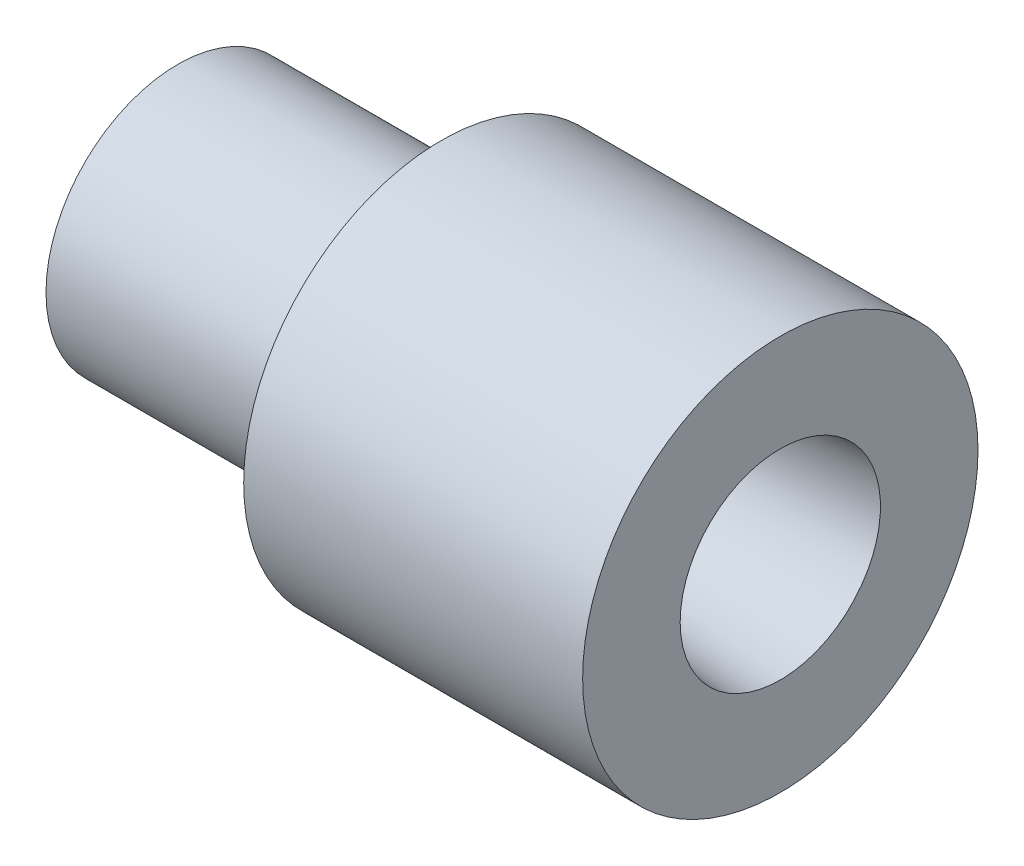
SolidWorks part; units mm, degrees
ref_plane "Front Plane" through (0, 0, 0) normal (0, 0, 1) x (1, 0, 0)
ref_plane "Top Plane" through (0, 0, 0) normal (0, 1, 0) x (1, 0, 0)
ref_plane "Right Plane" through (0, 0, 0) normal (1, 0, 0) x (0, 0, -1)
sketch "Sketch1" plane through (0, 0, 0) normal (0, 1, 0) x (1, 0, 0)
  line L0 (0, 0) -> (0, 2.286) construction
  line L1 (0, 2.286) -> (0, 6.35)
  line L2 (12.7, 9.525) -> (29.0323, 9.525)
  line L3 (29.0323, 9.525) -> (29.0323, 4.826)
  line L4 (29.0323, 4.826) -> (0, 2.286)
  line L5 (0, 0) -> (29.0323, 0) construction
  line L6 (29.0323, 0) -> (29.0323, 4.826) construction
  line L8 (12.7, 6.35) -> (12.7, 9.525)
  line L12 (0, 6.35) -> (12.7, 6.35)
  dimension "D1" = 2.286
  dimension "D2" = 4.826
  dimension "D3" = 5
  dimension "D4" = 9.525
  dimension "D5" = 6.35
  dimension "D6" = 12.7
revolve "Revolve1" add sketch "Sketch1" angle 360 about L5
equation "\"z\"= 8\t\t\t\t'number of blades"
equation "\"de\"= 0.43in\t\t\t'entrance eye diameter"
equation "\"de_length\"= 10mm\t\t'entrance eye consistent length"
equation "\"d_exit\"= 0.18in \t\t'throat aka d1"
equation "\"d2\"= 2.1in \t\t\t'outer diameter of the impeller"
equation "\"b2\"= .2in\t\t\t'tip height from disc surface at d2; slightly higher than d_exit"
equation "\"b1\"= \"b2\" + (\"d2\"/2 - \"de\"/2)*tan(\"theta\") \t\t\t'tip height from disc surface at inlet eye"
equation "\"theta\"= 12\t\t\t'angle of blades from inner to outer "
equation "\"ae\"= 3.14*(\"de\"^2)/4\t\t'entrance eye area'"
equation "\"ce\"= 3.14*\"de\"\t\t'entrance eye circumference"
equation "\"av_ratio\"= .325\t\t'ratio of av/ae at N_s of 470, range is .275 to .375, .325 ideal. High ratio means bigger area means smaller blades"
equation "\"av\"= \"ae\"*\"av_ratio\"\t\t'area between just two blades"
equation "\"s_open\"= \"av\"/\"b1\"\t\t'width of open area"
equation "\"s\"=\"ce\" - \"z\"*\"s_open\""
equation "\"min blade thickness\"= .15in"
equation "\"bearing OD\"= 30mm"
equation "\"bearing ID\"= 10mm"
equation "\"bearing depth\"= 9mm"
equation "\"bearing outer race thickness\"= 1mm"
equation "\"bearing inner race thickness\"= 1mm"
equation "\"bearing bore\"= \"bearing depth\" + 1mm"
equation "\"lower seal OD\"= .917in\t\t'this is https://www.mcmaster.com/#9281k121/=174001b"
equation "\"lower seal ID\"= .375in"
equation "\"lower seal depth\"= .625in + .218in"
equation "\"lower seal bore\"= \"lower seal depth\" + 1mm"
equation "\"upper seal OD\"= 1.125in\t'this is https://www.mcmaster.com/#5154t33/=173zuau, needs to be visually inspected before machining!"
equation "\"upper seal ID\"= 0.625in"
equation "\"upper seal depth\"= .25in\t'aka height; these values need to be confirmed by inspection!! We may want to compress the height."
equation "\"upper seal bore\"= \"upper seal depth\" + 1mm"
equation "\"big o-ring thickness\"= .139in"
equation "\"big o-ring OD\"= 2.734in"
equation "\"big o-ring ID\"= 3.012in"
equation "\"big o-ring groove depth\"= \"big o-ring thickness\"*4/5"
equation "\"impeller center height\"= \"impeller base thickness\" + \"b1\"\t'impeller height at de"
equation "\"impeller outer height\"= \"impeller base thickness\" + \"b2\"\t'impeller height at de"
equation "\"impeller upper clearance\"= .5mm"
equation "\"impeller horizontal clearance\"= (\"d2\"*1.15 - \"d2\")/2 \t\t'clearance based on D2-D3 ratio for circular volute, ranges 1.15 to 1.2"
equation "\"impeller bottom clearance\"= .5mm"
equation "\"impeller base thickness\"= 2mm"
equation "\"impeller dowel diameter\"= 2mm"
equation "\"impeller bolt head diameter\"= \"m4 head bore diameter\""
equation "\"impeller bolt head depth\"= 4mm"
equation "\"impeller bolt stop depth\"= 3mm"
equation "\"impeller bolt bore\"= \"m4 clearance\""
equation "\"impeller shaft bore depth\"= 12mm"
equation "\"impeller shaft bore\"= 8mm"
equation "\"impeller boss depth\"= \"impeller shaft bore depth\"+\"impeller bolt stop depth\"+\"impeller bolt head depth\"-\"impeller base thickness\""
equation "\"impeller boss diameter\"= \"upper seal ID\""
equation "\"impeller dowel length\"= 2mm*2 + \"impeller shaft bore\""
equation "\"coupler motor shaft hole ID\"= 8mm"
equation "\"coupler OD\"= 17mm"
equation "\"coupler length\"= 25mm"
equation "\"motor OD\"= 64mm"
equation "\"motor shaft diameter\"= 8mm"
equation "\"motor shaft pride\"= 32mm"
equation "\"motor to bearing plate distance\"= \"motor shaft pride\" + 2mm +\"coupler length\"/2"
equation "\"square plate bolt bore\"= \"m8 clearance\""
equation "\"square plate bolt head diameter\"= 13.5mm"
equation "\"square plate bolt head depth\"= 8mm"
equation "\"square plate bolt pattern diameter\"= 3.5in"
equation "\"motor mount center bore\"= \"coupler OD\"+ 4mm"
equation "\"motor mount post radius\"= ( 3 * \"square plate bolt bore\" ) / 2"
equation "\"motor mount m4 screw hole diameter\"= 4mm"
equation "\"motor mount m4 head diameter\"= 7.25mm"
equation "\"motor mount m4 head depth\"= 4mm"
equation "\"motor mount m4 pattern diamater\"= 30mm"
equation "\"motor mount plate thickness\"= 8mm + \"motor mount m4 head depth\""
equation "\"bearing plate stop ID\"= \"bearing OD\" - 4mm"
equation "\"bearing plate stop depth\"= 3mm"
equation "\"bearing plate thickness\"= \"bearing bore\" + \"bearing plate stop depth\" + \"shaft bearing stop length\""
equation "\"lower seal plate lip depth\"= 2mm"
equation "\"lower seal plate lip ID\"= \"lower seal OD\" - 3mm"
equation "\"lower seal plate thickness\"= \"lower seal plate lip depth\" + \"lower seal bore\""
equation "\"shaft coupler section diameter\"= 8mm"
equation "\"shaft coupler section length\"= \"motor to bearing plate distance\" - \"motor shaft pride\" - 2mm"
equation "\"shaft bearing section diameter\"= \"bearing ID\""
equation "\"shaft bearing section length\"= \"bearing plate stop depth\" + \"bearing depth\""
equation "\"shaft bearing stop diameter\"= \"bearing ID\" + 4mm"
equation "\"shaft bearing stop length\"= 3mm"
equation "\"shaft lower seal section diameter\"= \"lower seal ID\""
equation "\"shaft lower seal section length\"= \"lower seal plate thickness\" + 1mm"
equation "\"shaft impeller section diameter\"= \"impeller shaft bore\""
equation "\"shaft impeller section length\"= \"upper seal plate thickness\" + \"upper seal plate riser\" + \"impeller bottom clearance\" + \"impeller base thickness\" - \"impeller bolt head depth\" - \"impeller bolt stop depth\""
equation "\"upper seal plate thickness\"= \"upper seal plate pressure hole diameter\"+10mm"
equation "\"upper seal plate lip ID\"= \"upper seal OD\" - 3mm"
equation "\"upper seal plate riser\"= 6.59mm \t\t'this number needs to be read from the housing file"
equation "\"upper seal plate pressure hole diameter\"= .125in\t'this is 1/8 drill "
equation "\"upper seal plate pressure tap diameter\"= .328125in \t'this is 21/64 drill for a 1/8 ANPT tap"
equation "\"upper seal plate pressure tap grip\"= 5mm\t\t'this is the area around the tap so it doesn't crack"
equation "\"upper seal plate pressure tap depth\"= 12mm"
equation "\"impeller cavity center height\"= \"impeller bottom clearance\" + \"impeller upper clearance\" + \"impeller center height\""
equation "\"impeller cavity diameter\"= 2 * \"impeller horizontal clearance\" + \"d2\" \t\t\t\t\t\t\t\t\t'called D3 analytically"
equation "\"impeller cavity outer height\"= \"impeller bottom clearance\" + \"impeller upper clearance\" + \"impeller base thickness\" + \"b2\" \t\t'this is height at impeller diameter d2, not at d3"
equation "\"impeller housing thickness\"= \"impeller housing exit threaded diameter\" + 2*\"impeller housing outlet grip\""
equation "\"impeller housing diameter\"= \"square plate bolt pattern diameter\" + 2*\"motor mount post radius\""
equation "\"impeller housing bolt count\"= 6"
equation "\"impeller housing bolt diameter\"= \"m6 clearance\""
equation "\"impeller housing bolt pattern diameter\"= 3.5in"
equation "\"impeller housing threaded inlet diameter\"= 0.515625in \t'this is the 33/64 drill size for 9/16-18 fitting, expecting swagelok SS-8FK0-1-6STH fitting"
equation "\"impeller housing threaded inlet depth\"= 10mm"
equation "\"impeller housing exit threaded diameter\"= 0.515625in \t\t'this is the 33/64 drill size for 9/16-18 fitting, expecting swagelok SS-8FK0-1-6STH fitting"
equation "\"impeller housing exit threaded depth\"= 10mm"
equation "\"impeller housing diffuser conical angle\"=10"
equation "\"impeller housing diffuser tangent angle\"=5"
equation "\"impeller housing diffuser final diameter\"= .38in\t\t'aka d2'"
equation "\"impeller housing outlet grip\"= 5mm"
equation "\"end mill size\"= 0.375in\t'for 3/8 endmill"
equation "\"m4 clearance\"= 0.171875in \t'this is 11/64 bit for 4.36mm"
equation "\"m4 tap\"= 0.125in\t\t'this is 1/8 bit for 3.17mm"
equation "\"m4 head bore diameter\"= 7.5mm"
equation "\"m4 head bore depth\"= 5mm\t'actual is ~4mm"
equation "\"m6 clearance\"= 0.234375in\t'this is 15/64 bit = 5.95mm, could use 6mm bit, B bit for 6.04mm or 1/4 bit for 6.35mm"
equation "\"m6 tap\"= 5mm\t\t\t'5mm is appropriate, could use 13/64 or #5,6,7"
equation "\"m6 head bore diameter\"= 11mm\t\t"
equation "\"m6 head bore depth\"= 7mm\t'actual is 6mm"
equation "\"m8 clearance\"= 0.3125in\t'this is 5/16in for 7.93mm, could use 8mm, O,P, or 21/64"
equation "\"m8 tap\"= 0.265625in\t\t'this is 17/64 for 6.746875mm"
equation "\"m8 head bore diameter\"= 14mm"
equation "\"m8 head bore depth\"= 9mm\t'actual is 8mm"
equation "\"D1@Sketch1\"=\"d_exit\"/2"
equation "\"D2@Sketch1\"=\"impeller housing diffuser final diameter\"/2"
equation "\"diffuser cartridge OD\"=.75in"
equation "\"D4@Sketch1\"=\"diffuser cartridge OD\"/2"
